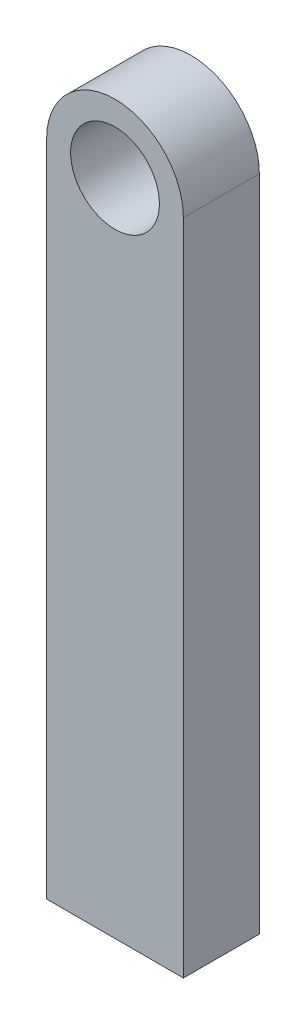
SolidWorks part; units mm, degrees
ref_plane "Front Plane" through (0, 0, 0) normal (0, 0, 1) x (1, 0, 0)
ref_plane "Top Plane" through (0, 0, 0) normal (0, 1, 0) x (1, 0, 0)
ref_plane "Right Plane" through (0, 0, 0) normal (1, 0, 0) x (0, 0, -1)
sketch "Sketch1" plane through (0, 0, 0) normal (0, 0, 1) x (1, 0, 0)
  line L1 (0, 0) -> (54, 0)
  line L2 (0, 0) -> (0, 260)
  line L4 (54, 0) -> (54, 260)
  arc A0 (54, 260) -> (0, 260) centre (27, 260) ccw
  circle A1 centre (27, 260) radius 17.525
  dimension "D3" = 35.05
  dimension "D1" = 54
  dimension "D2" = 260
extrude "Boss-Extrude1" add sketch "Sketch1" along normal blind 30
